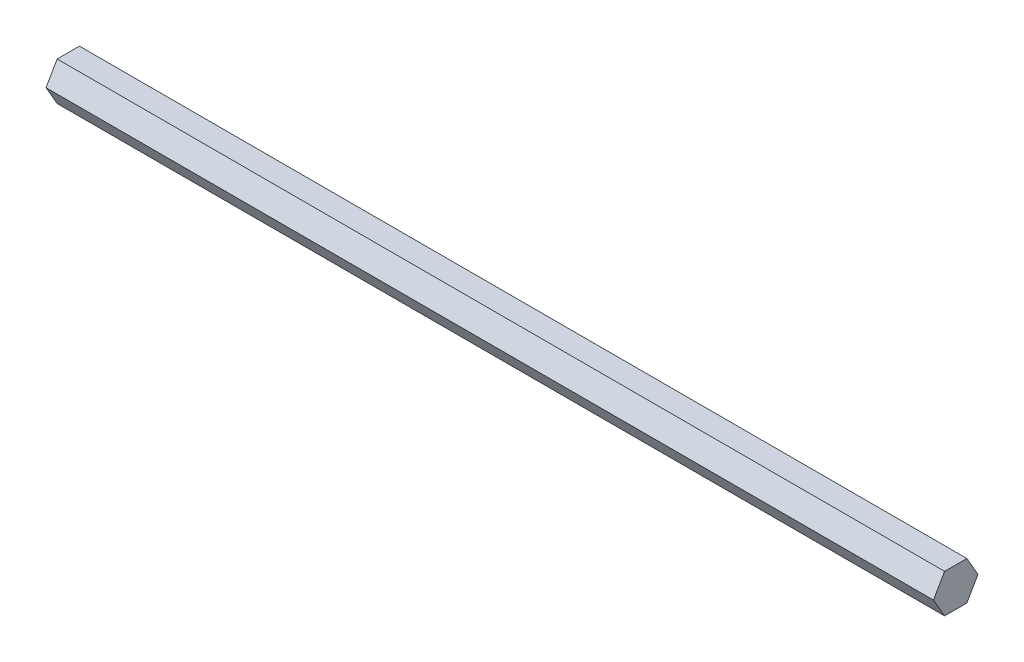
SolidWorks part; units mm, degrees
ref_plane "Front Plane" through (0, 0, 0) normal (0, 0, 1) x (1, 0, 0)
ref_plane "Top Plane" through (0, 0, 0) normal (0, 1, 0) x (1, 0, 0)
ref_plane "Right Plane" through (0, 0, 0) normal (1, 0, 0) x (0, 0, -1)
sketch "Sketch1" plane through (0, 0, 0) normal (1, 0, 0) x (0, 0, -1)
  line L1 (7.3323, 0) -> (3.6662, 6.35)
  line L2 (3.6662, 6.35) -> (-3.6662, 6.35)
  line L3 (-3.6662, 6.35) -> (-7.3323, 0)
  line L4 (-7.3323, 0) -> (-3.6662, -6.35)
  line L5 (-3.6662, -6.35) -> (3.6662, -6.35)
  line L6 (3.6662, -6.35) -> (7.3323, 0)
  circle A0 centre (0, 0) radius 6.35 construction
  dimension "D1" = 12.7
extrude "Boss-Extrude1" add sketch "Sketch1" along normal blind 292.1
